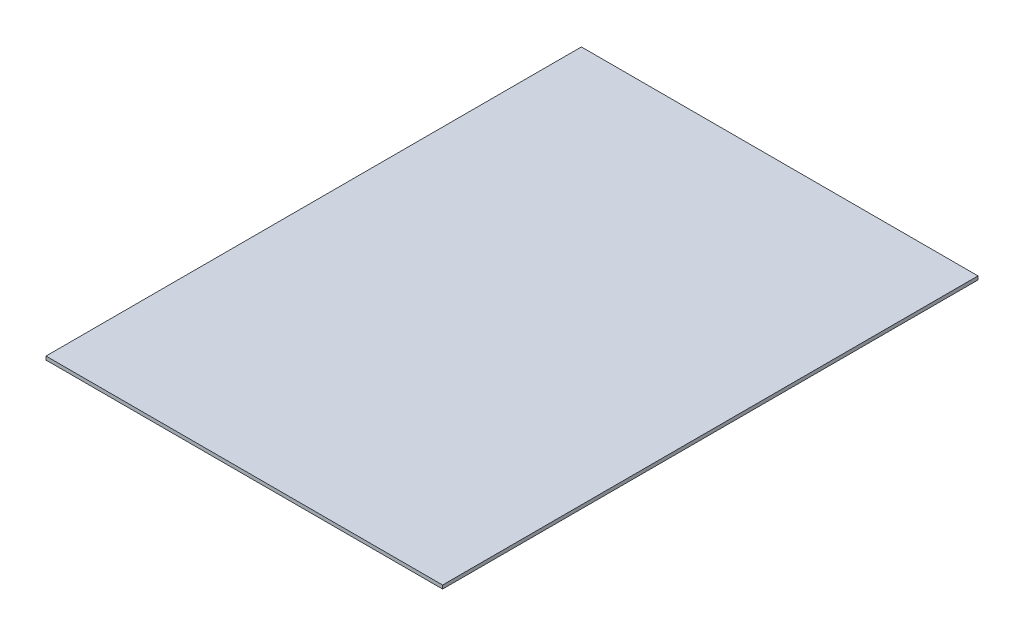
SolidWorks part; units mm, degrees
material "PC High Viscosity"
ref_plane "Front Plane" through (0, 0, 0) normal (0, 0, 1) x (1, 0, 0)
ref_plane "Top Plane" through (0, 0, 0) normal (0, 1, 0) x (1, 0, 0)
ref_plane "Right Plane" through (0, 0, 0) normal (1, 0, 0) x (0, 0, -1)
sketch "Sketch1" plane through (0, 0, 0) normal (0, 1, 0) x (1, 0, 0)
  line L1 (-88.9, 120.015) -> (88.9, 120.015)
  line L2 (-88.9, 120.015) -> (-88.9, -120.015)
  line L3 (-88.9, -120.015) -> (88.9, -120.015)
  line L4 (88.9, 120.015) -> (88.9, -120.015)
  line L5 (-88.9, 120.015) -> (88.9, -120.015) construction
  line L6 (-88.9, -120.015) -> (88.9, 120.015) construction
  point P0 (0, 0)
  dimension "D1" = 177.8
  dimension "D2" = 240.03
extrude "Boss-Extrude1" add sketch "Sketch1" along normal blind 1.5875
